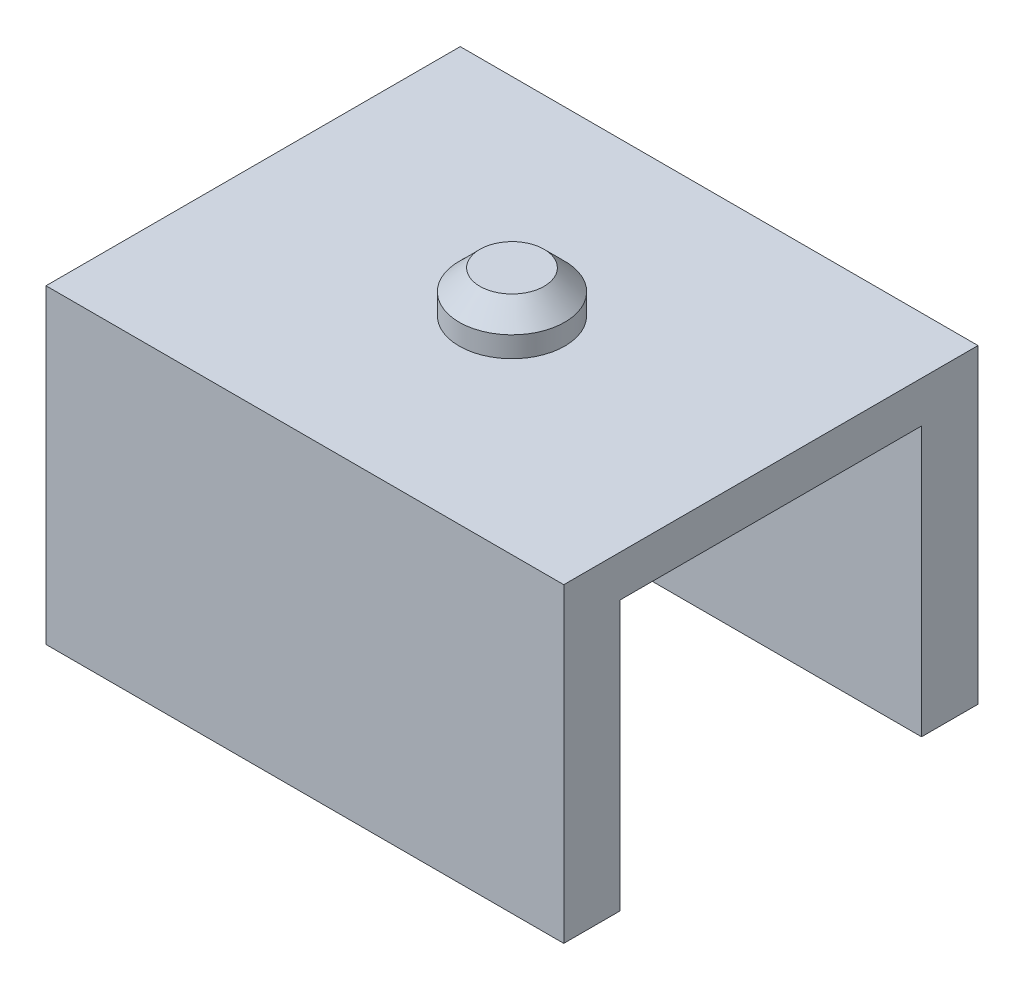
SolidWorks part; units mm, degrees
ref_plane "Top" through (0, 0, 0) normal (0, 0, 1) x (1, 0, 0)
ref_plane "Front" through (0, 0, 0) normal (0, 1, 0) x (1, 0, 0)
ref_plane "Right" through (0, 0, 0) normal (1, 0, 0) x (0, 0, -1)
sketch "Sketch1" plane through (0, 0, 0) normal (0, 0, 1) x (1, 0, 0)
  line L0 (0, 0) -> (0, 15)
  line L1 (0, 15) -> (25, 15)
  line L2 (25, 15) -> (25, 0)
  line L3 (25, 0) -> (0, 0)
  dimension "D1" = 25
  dimension "D2" = 15
extrude "Boss-Extrude1" add sketch "Sketch1" along normal blind 20
sketch "Sketch2" plane through (0, 0, 0) normal (0, -1, 0) x (1, 0, 0)
  line L0 (0, 2.725) -> (25, 2.725)
  line L1 (0, 20) -> (0, 0) construction
  line L2 (25, 20) -> (25, 0) construction
  line L3 (25, 2.725) -> (25, 17.275)
  line L4 (25, 17.275) -> (0, 17.275)
  line L5 (0, 17.275) -> (0, 2.725)
  line L6 (0, 0) -> (25, 0) construction
  dimension "D1" = 2.725
  dimension "D2" = 14.55
extrude "Cut-Extrude1" cut sketch "Sketch2" against normal blind 13
sketch "Sketch4" plane through (0, 15, 0) normal (0, 1, 0) x (1, 0, 0)
  line L0 (25, 0) -> (0, 0) construction
  line L2 (0, -20) -> (0, 0) construction
  circle A0 centre (12.5, -10) radius 2.55
  point P6 (0, 0)
  dimension "D2" = 12.5
  dimension "D3" = 5.1
  dimension "D1" = 10
extrude "Boss-Extrude2" add sketch "Sketch4" along normal blind 2
chamfer "Chamfer1" distance 1 angle 45 1 edges at (12.5, 17, 12.55)
